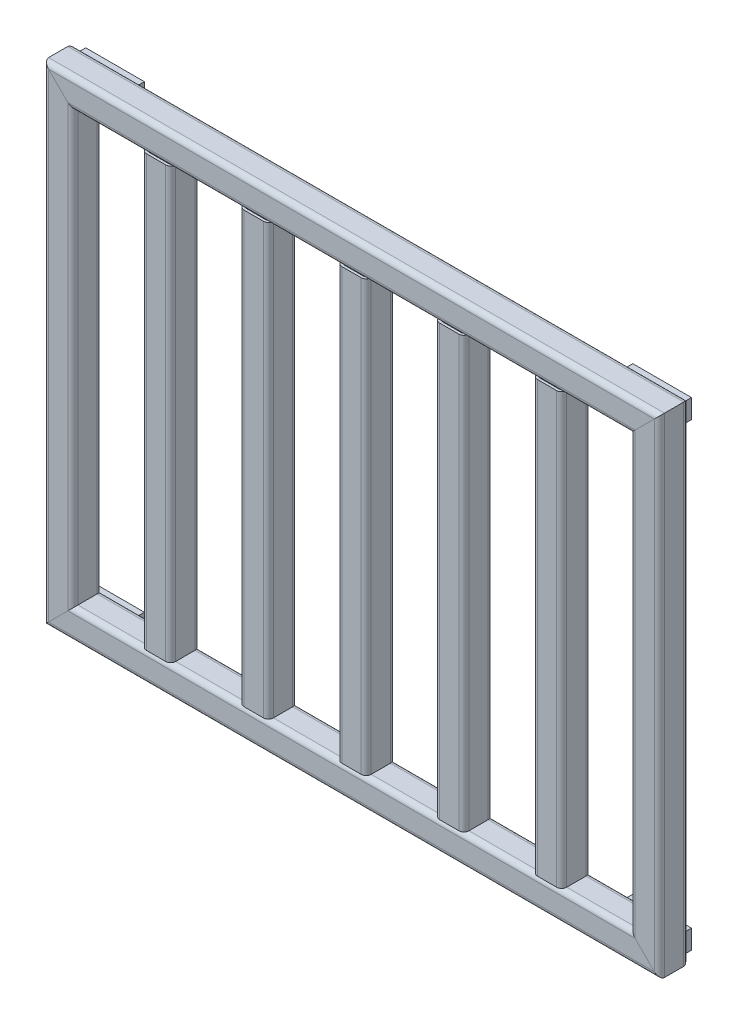
SolidWorks part; units mm, degrees
material "1.4003 (X2CrNi12)"
ref_plane "Ön Düzlem" through (0, 0, 0) normal (0, 0, 1) x (1, 0, 0)
ref_plane "Üst Düzlem" through (0, 0, 0) normal (0, 1, 0) x (1, 0, 0)
ref_plane "Sağ Düzlem" through (0, 0, 0) normal (1, 0, 0) x (0, 0, -1)
sketch "Çizim1" plane through (0, 0, 0) normal (0, 0, 1) x (1, 0, 0)
  line L0 (-200, 235) -> (-200, -235)
  line L1 (-300, 235) -> (300, 235)
  line L2 (-300, 235) -> (-300, -235)
  line L3 (-300, -235) -> (300, -235)
  line L4 (300, 235) -> (300, -235)
  line L5 (-300, 235) -> (300, -235) construction
  line L6 (-300, -235) -> (300, 235) construction
  line L7 (-100, 235) -> (-100, -235)
  line L8 (0, 235) -> (0, -235)
  line L9 (100, 235) -> (100, -235)
  line L10 (200, 235) -> (200, -235)
  point P0 (0, 0)
  dimension "D1" = 600
  dimension "D2" = 470
  dimension "D3" = 100
  dimension "D4" = 100
  dimension "D5" = 100
  dimension "D6" = 100
other "Kare tüp 30 X 30 X 2.6(1)"
ref_plane "Düzlem1" through (300, 235, 0) normal (0, -1, 0) x (1, 0, 0)
sketch "Sketch1" plane through (300, 235, 0) normal (0, -1, 0) x (1, 0, 0)
  line L0 (-9.8, -12.4) -> (9.8, -12.4)
  line L1 (-12.4, -9.8) -> (-12.4, 9.8)
  line L2 (9.8, 12.4) -> (-9.8, 12.4)
  line L3 (12.4, 9.8) -> (12.4, -9.8)
  line L4 (-9.8, -15) -> (9.8, -15)
  line L5 (-15, -9.8) -> (-15, 9.8)
  line L6 (9.8, 15) -> (-9.8, 15)
  line L7 (15, 9.8) -> (15, -9.8)
  arc A0 (15, 9.8) -> (9.8, 15) centre (9.8, 9.8) ccw
  arc A1 (9.8, -15) -> (15, -9.8) centre (9.8, -9.8) ccw
  arc A2 (-15, -9.8) -> (-9.8, -15) centre (-9.8, -9.8) ccw
  arc A3 (-9.8, 15) -> (-15, 9.8) centre (-9.8, 9.8) ccw
  arc A4 (-9.8, 12.4) -> (-12.4, 9.8) centre (-9.8, 9.8) ccw
  arc A5 (12.4, 9.8) -> (9.8, 12.4) centre (9.8, 9.8) ccw
  arc A6 (9.8, -12.4) -> (12.4, -9.8) centre (9.8, -9.8) ccw
  arc A7 (-12.4, -9.8) -> (-9.8, -12.4) centre (-9.8, -9.8) ccw
  point P0 (-15, 0)
  point P1 (15, 0)
  point P2 (0, 15)
  point P3 (0, -15)
  point P4 (0, 0)
  point P5 (-15, -15)
  point P6 (15, -15)
  point P7 (15, 15)
  point P8 (-15, 15)
  point P33 (0, 0)
  dimension "D1" = 5.2
  dimension "Thickness" = 2.6
  dimension "V_leg" = 30
sketch "Çizim2" plane through (0, 0, -15) normal (0, 0, -1) x (-1, 0, 0)
  line L0 (309.8, -244.8) -> (-309.8, -244.8) construction
  line L1 (-309.8, -244.8) -> (-249.8, -244.8)
  line L2 (-309.8, -244.8) -> (-309.8, -225.2)
  line L3 (-309.8, -225.2) -> (-249.8, -225.2)
  line L4 (-249.8, -244.8) -> (-249.8, -225.2)
  line L5 (290.2, -225.2) -> (-290.2, -225.2) construction
  line L6 (-309.8, -244.8) -> (-309.8, 244.8) construction
  line L7 (-290.2, 225.2) -> (290.2, 225.2) construction
  line L8 (-309.8, 225.2) -> (-249.8, 225.2)
  line L9 (-309.8, 225.2) -> (-309.8, 244.8)
  line L10 (-309.8, 244.8) -> (-249.8, 244.8)
  line L11 (-249.8, 225.2) -> (-249.8, 244.8)
  line L12 (-309.8, 244.8) -> (309.8, 244.8) construction
  line L13 (309.8, 244.8) -> (309.8, -244.8) construction
  line L14 (309.8, 225.2) -> (249.8, 225.2)
  line L15 (309.8, 225.2) -> (309.8, 244.8)
  line L16 (309.8, 244.8) -> (249.8, 244.8)
  line L17 (249.8, 225.2) -> (249.8, 244.8)
  line L19 (309.8, -244.8) -> (249.8, -244.8)
  line L20 (309.8, -244.8) -> (309.8, -225.2)
  line L21 (309.8, -225.2) -> (249.8, -225.2)
  line L22 (249.8, -244.8) -> (249.8, -225.2)
  dimension "D1" = 60
  dimension "D2" = 60
  dimension "D3" = 60
  dimension "D4" = 60
extrude "Yükseklik-Ekstrüzyon1" add sketch "Çizim2" along normal blind 8 separate body
